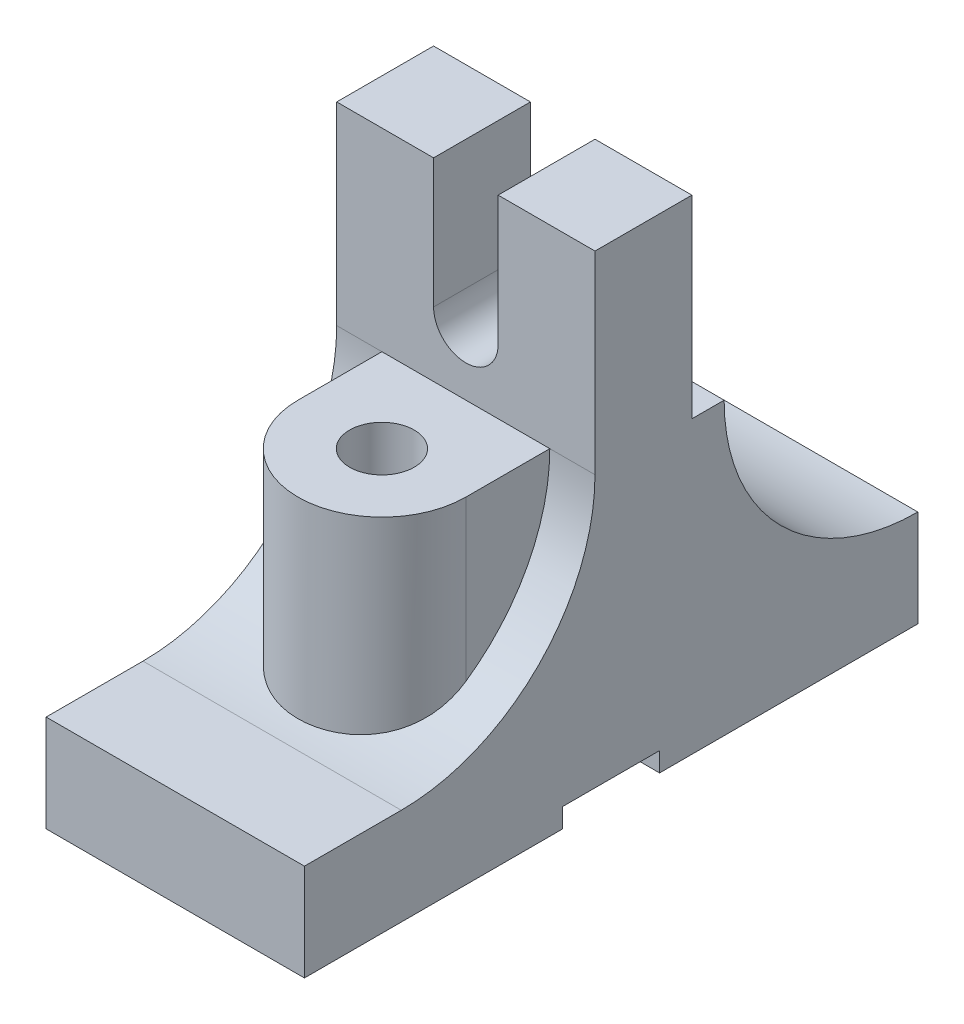
SolidWorks part; units mm, degrees
ref_plane "Front Plane" through (0, 0, 0) normal (0, 0, 1) x (1, 0, 0)
ref_plane "Top Plane" through (0, 0, 0) normal (0, 1, 0) x (1, 0, 0)
ref_plane "Right Plane" through (0, 0, 0) normal (1, 0, 0) x (0, 0, -1)
sketch "Sketch1" plane through (0, 0, 0) normal (1, 0, 0) x (0, 0, -1)
  line L0 (0, 86.1481) -> (0, -28.1173) construction
  line L1 (-47.5, 0) -> (-7.5, 0)
  line L2 (-7.5, 0) -> (-7.5, 3)
  line L3 (-7.5, 3) -> (7.5, 3)
  line L4 (7.5, 3) -> (7.5, 0)
  line L5 (7.5, 0) -> (47.5, 0)
  line L6 (47.5, 0) -> (47.5, 15)
  line L8 (-47.5, 15) -> (-47.5, 0)
  line L14 (-47.5, 15) -> (-32.5, 15)
  line L15 (17.5, 45) -> (12.5, 45)
  line L16 (12.5, 45) -> (-2.5, 45)
  arc A2 (17.5, 45) -> (47.5, 15) centre (47.5, 45) ccw
  arc A3 (-32.5, 15) -> (-2.5, 45) centre (-32.5, 45) ccw
  dimension "D7" = 5
  dimension "D6" = 30
  dimension "D1" = 15
  dimension "D2" = 40
  dimension "D3" = 15
  dimension "D4" = 3
  dimension "D5" = 7.5
extrude "Boss-Extrude4" add sketch "Sketch1" along normal mid plane 40
sketch "Sketch6" plane through (0, 45, 0) normal (0, 1, 0) x (1, 0, 0)
  line L0 (20, -2.5) -> (-20, -2.5) construction
  line L2 (-13, -15.5) -> (-13, -2.5)
  line L3 (13, -15.5) -> (13, -2.5)
  line L7 (-20, 17.5) -> (-20, -2.5)
  line L8 (-20, -2.5) -> (20, -2.5)
  line L9 (20, -2.5) -> (20, 17.5)
  line L10 (20, 17.5) -> (-20, 17.5)
  line L12 (-13, -2.5) -> (13, -2.5)
  arc A0 (-13, -15.5) -> (13, -15.5) centre (0, -15.5) ccw
  dimension "D2" = 26
  dimension "D1" = 0
extrude "Boss-Extrude5" add sketch "Sketch6" against normal up to next
sketch "Sketch7" plane through (0, 45, 0) normal (0, 1, 0) x (1, 0, 0)
  circle A0 centre (0, -15.5) radius 5
  dimension "D1" = 10
extrude "Cut-Extrude1" cut sketch "Sketch7" against normal through all
sketch "Sketch8" plane through (20, 0, 0) normal (1, 0, 0) x (0, 0, -1)
  line L0 (-2.5, 45) -> (-2.5, 75)
  line L1 (-2.5, 75) -> (12.5, 75)
  line L2 (12.5, 75) -> (12.5, 45)
  line L3 (17.5, 45) -> (-2.5, 45) construction
  line L4 (-2.5, 45) -> (12.5, 45)
  dimension "D1" = 30
  dimension "D2" = 15
extrude "Boss-Extrude6" add sketch "Sketch8" against normal blind 40
sketch "Sketch9" plane through (0, 0, 2.5) normal (0, 0, 1) x (1, 0, 0)
  line L0 (0, 81.8899) -> (0, -5.2086) construction
  line L1 (-20, 75) -> (20, 75) construction
  line L2 (-5, 75) -> (5, 75)
  line L3 (-5, 75) -> (-5, 55)
  line L5 (5, 75) -> (5, 55)
  arc A0 (-5, 55) -> (5, 55) centre (0, 55) ccw
  dimension "D1" = 20
  dimension "D2" = 10
extrude "Cut-Extrude2" cut sketch "Sketch9" against normal up to next
